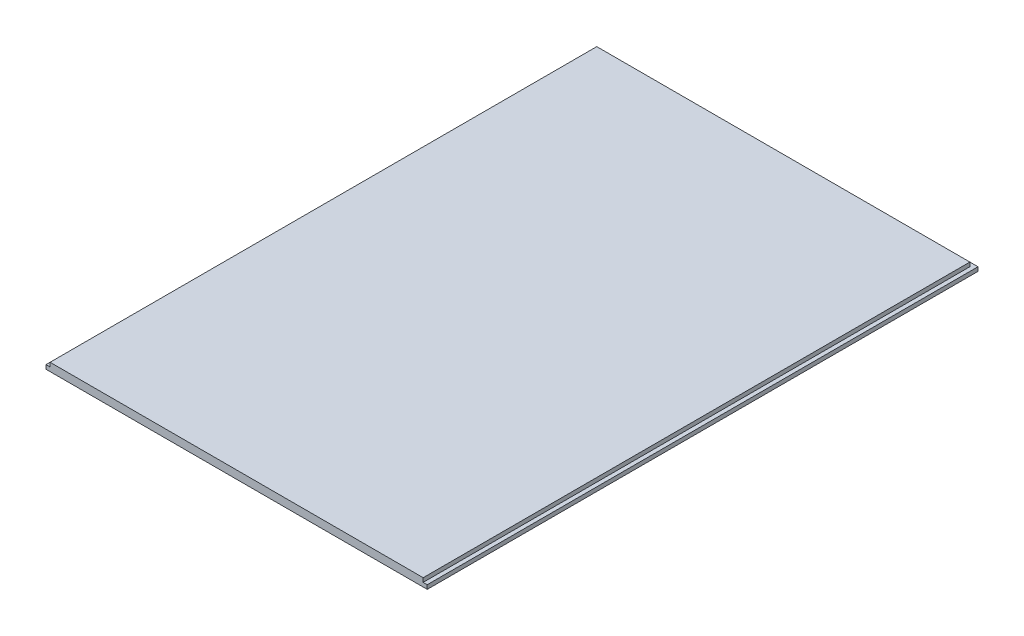
SolidWorks part; units mm, degrees
material "Perspex (TM) GS Acrylic Cast Sheet"
ref_plane "Front Plane" through (0, 0, 0) normal (0, 0, 1) x (1, 0, 0)
ref_plane "Top Plane" through (0, 0, 0) normal (0, 1, 0) x (1, 0, 0)
ref_plane "Right Plane" through (0, 0, 0) normal (1, 0, 0) x (0, 0, -1)
sketch "Sketch1" plane through (0, 0, 0) normal (0, 1, 0) x (1, 0, 0)
  line L1 (0, 0) -> (298.45, 0)
  line L2 (0, 0) -> (0, 431.165)
  line L3 (0, 431.165) -> (298.45, 431.165)
  line L4 (298.45, 0) -> (298.45, 431.165)
  dimension "D1" = 298.45
  dimension "D2" = 431.165
extrude "Boss-Extrude1" add sketch "Sketch1" along normal blind 6.35
sketch "Sketch2" plane through (0, 6.35, 0) normal (0, 1, 0) x (1, 0, 0)
  line L0 (0, 0) -> (298.45, 0) construction
  line L2 (3.175, 0) -> (3.175, 427.99)
  line L3 (3.175, 427.99) -> (295.275, 427.99)
  line L4 (295.275, 0) -> (295.275, 427.99)
  line L5 (0, 431.165) -> (0, 0) construction
  line L6 (298.45, 431.165) -> (0, 431.165) construction
  line L7 (298.45, 0) -> (298.45, 431.165) construction
  line L8 (3.175, 0) -> (0, 0)
  line L9 (0, 0) -> (0, 431.165)
  line L10 (0, 431.165) -> (298.45, 431.165)
  line L11 (298.45, 431.165) -> (298.45, 0)
  point P20 (295.275, -0.9905)
  point P21 (0, 0)
  line M4 (0, 431.165) -> (0, 0)
  line M5 (0, 0) -> (298.45, 0)
  line M6 (298.45, 0) -> (298.45, 431.165)
  line M7 (298.45, 431.165) -> (0, 431.165)
  dimension "D1" = 3.175
  dimension "D2" = 3.175
  dimension "D3" = 3.175
extrude "Cut-Extrude1" cut sketch "Sketch2" against normal blind 3.175 and the other way through all contours L4 L2 L3 M5 M6 M7 M4
equation "\"D2@Sketch1\"=16.85in+.125in"
equation "\"D2@Sketch2\"=\"D1@Sketch2\""
equation "\"D3@Sketch2\"=\"D1@Sketch2\""
